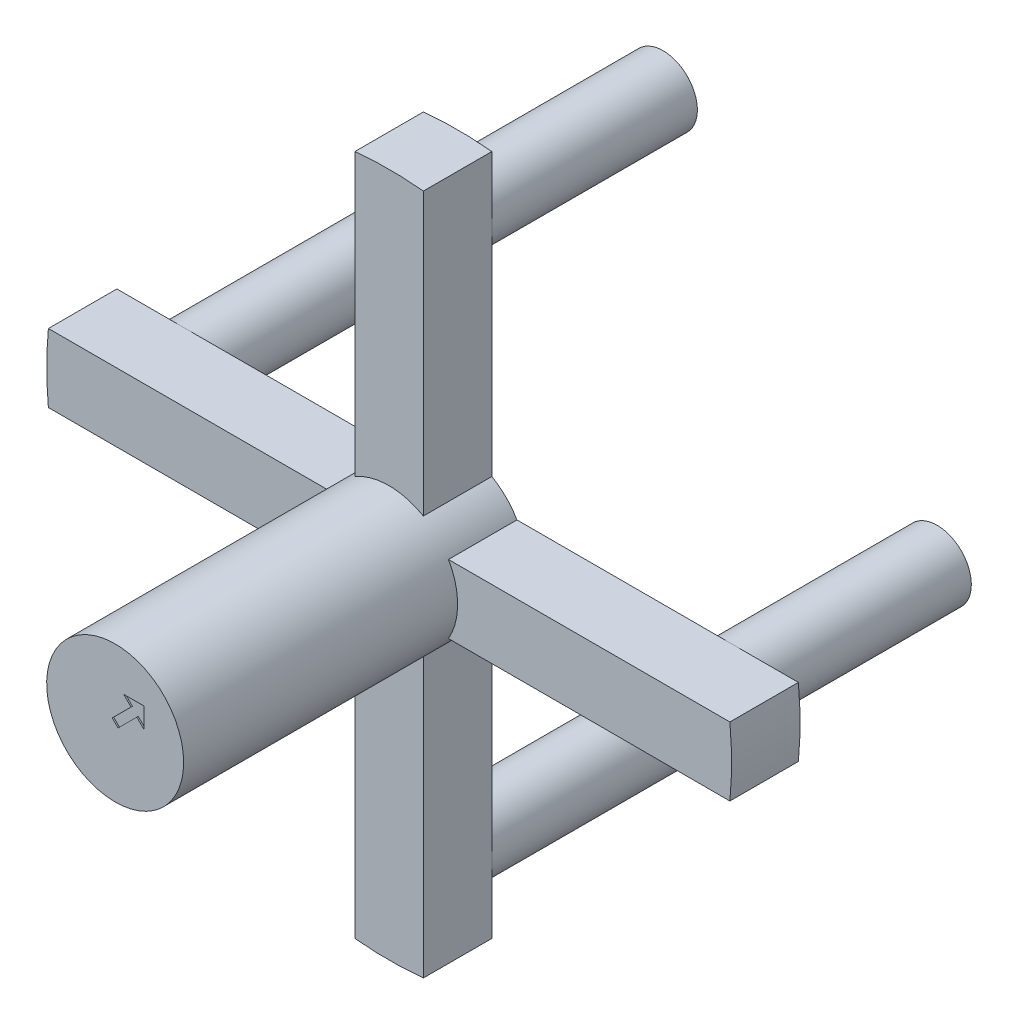
SolidWorks part; units mm, degrees
ref_plane "Front Plane" through (0, 0, 0) normal (0, 0, 1) x (1, 0, 0)
ref_plane "Top Plane" through (0, 0, 0) normal (0, 1, 0) x (1, 0, 0)
ref_plane "Right Plane" through (0, 0, 0) normal (1, 0, 0) x (0, 0, -1)
sketch "Sketch1" plane through (0, 0, 0) normal (0, 0, 1) x (1, 0, 0)
  circle A0 centre (0, 0) radius 5
extrude "Boss-Extrude1" add sketch "Sketch1" along normal blind 20
sketch "Sketch2" plane through (0, 0, 0) normal (0, 0, -1) x (-1, 0, 0)
  line L0 (0, 0) -> (0, 25) construction
  line L1 (2.5, 0) -> (2.5, 25)
  line L2 (-2.5, 0) -> (-2.5, 25)
  line L3 (0, -2.5) -> (25, -2.5)
  line L4 (0, 2.5) -> (25, 2.5)
  line L5 (-2.5, 0) -> (-2.5, -25)
  line L6 (2.5, 0) -> (2.5, -25)
  line L7 (0, 2.5) -> (-25, 2.5)
  line L8 (0, -2.5) -> (-25, -2.5)
  circle A0 centre (0, 0) radius 25
  point P23 (0, 0)
  dimension "D1" = 2.5
  dimension "D2" = 2.5
  dimension "D3" = 4
extrude "Boss-Extrude3" add sketch "Sketch2" along normal blind 5
sketch "Sketch3" plane through (0, 0, -5) normal (0, 0, -1) x (-1, 0, 0)
  circle A0 centre (-20, 0) radius 2.5
  circle A1 centre (0, 20) radius 2.5
  circle A2 centre (20, 0) radius 2.5
  circle A3 centre (0, -20) radius 2.5
  point P12 (0, 0)
  dimension "D1" = 20
  dimension "D2" = 4
extrude "Boss-Extrude4" add sketch "Sketch3" along normal blind 15
sketch "Sketch4" plane through (0, 0, 20) normal (0, 0, 1) x (1, 0, 0)
  line L0 (0, 0) -> (-2.1213, 2.1213) construction
  line L1 (-2.1213, 2.1213) -> (-0.6213, 2.1213)
  line L2 (-0.6213, 2.1213) -> (-2.1213, 0.6213)
  line L3 (-2.1213, 0.6213) -> (-2.1213, 2.1213)
  line L4 (0.2121, 0.2121) -> (-1.9092, 2.3335)
  line L5 (-0.2121, -0.2121) -> (-2.3335, 1.9092)
  line L6 (-0.2121, -0.2121) -> (0.2121, 0.2121)
  line L7 (0.6213, 2.1213) -> (2.1213, 2.1213)
  line L8 (2.1213, 2.1213) -> (2.1213, 0.6213)
  line L9 (2.1213, 0.6213) -> (0.6213, 2.1213)
  line L10 (0.2121, -0.2121) -> (2.3335, 1.9092)
  line L11 (-0.2121, 0.2121) -> (1.9092, 2.3335)
  line L12 (-0.2121, 0.2121) -> (0.2121, -0.2121)
  point P19 (0, 0)
  dimension "D1" = 0.3
  dimension "D3" = 2
  dimension "D2" = 0.3
extrude "Cut-Extrude2" cut sketch "Sketch4" against normal blind 0.1 contours L9 L11 L7 | L11 L9 L10 L8 L7 | L10 L9 L8 | L6 L12 L10 L9 L11 L4 | L11 L12 L6 L4
